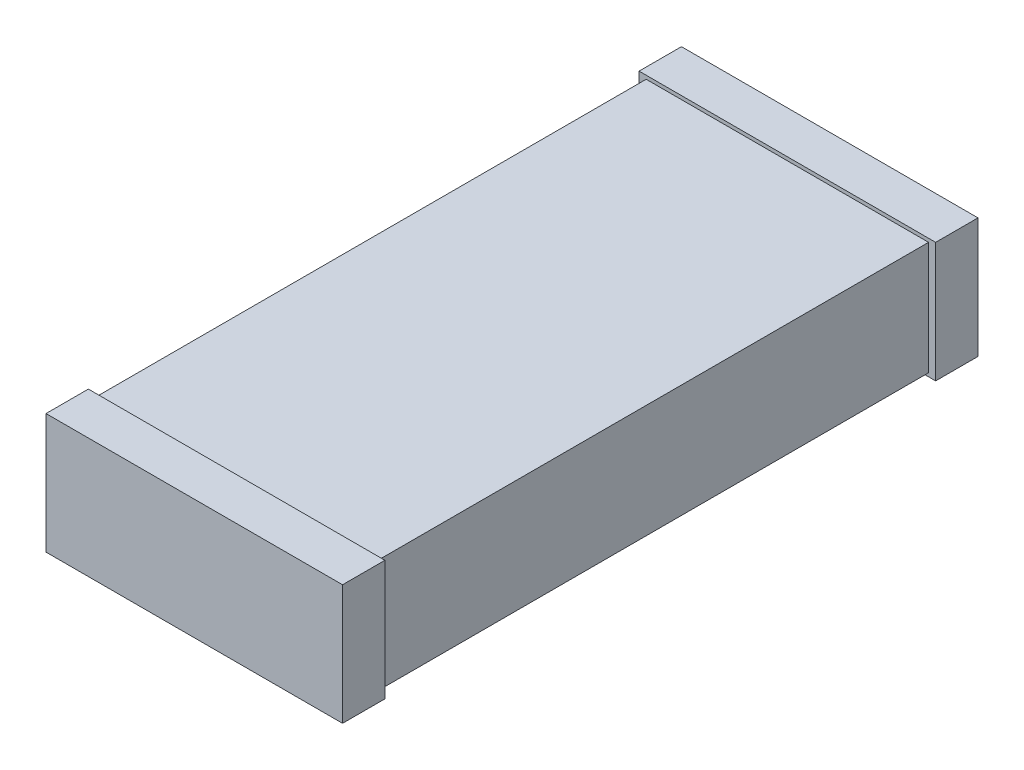
SolidWorks part; units mm, degrees
ref_plane "Спереди" through (0, 0, 0) normal (0, 0, 1) x (1, 0, 0)
ref_plane "Сверху" through (0, 0, 0) normal (0, 1, 0) x (1, 0, 0)
ref_plane "Справа" through (0, 0, 0) normal (1, 0, 0) x (0, 0, -1)
sketch "Эскиз1" plane through (0, 0, 0) normal (0, 0, 1) x (1, 0, 0)
  line L1 (-1, 0.4) -> (1, 0.4)
  line L2 (-1, 0.4) -> (-1, -0.4)
  line L3 (-1, -0.4) -> (1, -0.4)
  line L4 (1, 0.4) -> (1, -0.4)
  line L5 (-1, 0.4) -> (1, -0.4) construction
  line L6 (-1, -0.4) -> (1, 0.4) construction
  point P0 (0, 0)
extrude "Бобышка-Вытянуть1" add sketch "Эскиз1" along normal blind 1.95
sketch "Эскиз2" plane through (0, 0, 1.95) normal (0, 0, 1) x (1, 0, 0)
  line L1 (-1.05, -0.425) -> (1.05, -0.425)
  line L2 (-1.05, -0.425) -> (-1.05, 0.425)
  line L3 (-1.05, 0.425) -> (1.05, 0.425)
  line L4 (1.05, -0.425) -> (1.05, 0.425)
  line L5 (-1.05, -0.425) -> (1.05, 0.425) construction
  line L6 (-1.05, 0.425) -> (1.05, -0.425) construction
  point P0 (0, 0)
extrude "Бобышка-Вытянуть2" add sketch "Эскиз2" along normal blind 0.3
mirror "Зеркальное отражение1" of "Бобышка-Вытянуть1", "Бобышка-Вытянуть2"
